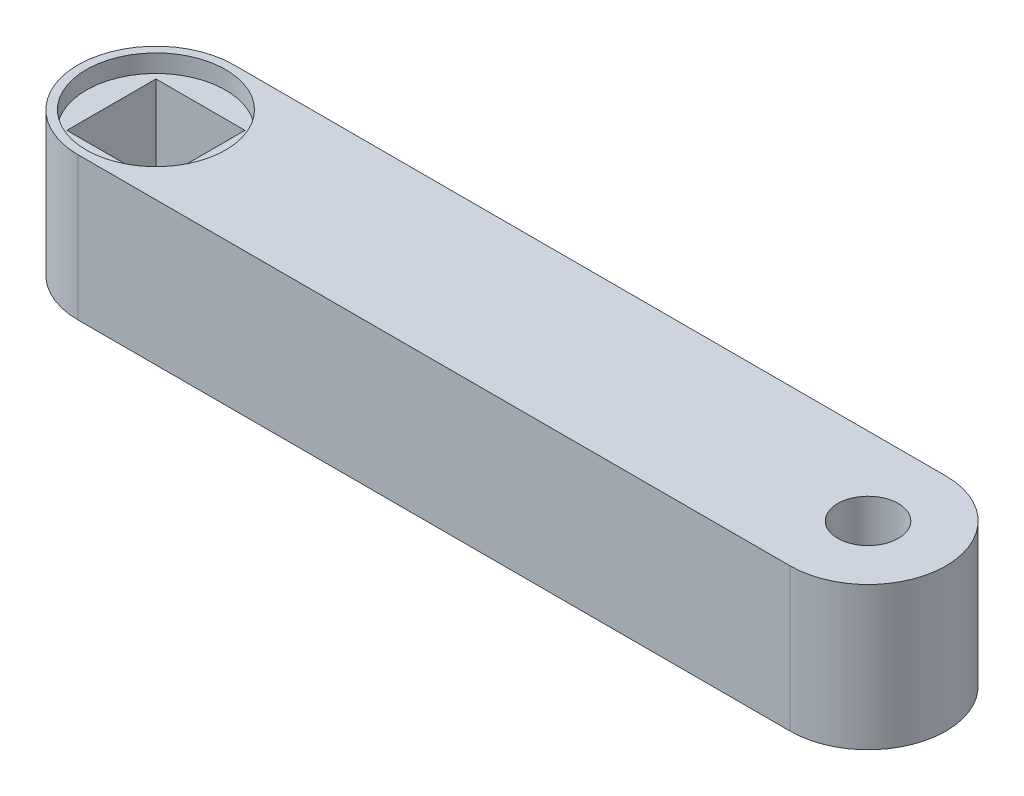
SolidWorks part; units mm, degrees
ref_plane "Front Plane" through (0, 0, 0) normal (0, 0, 1) x (1, 0, 0)
ref_plane "Top Plane" through (0, 0, 0) normal (0, 1, 0) x (1, 0, 0)
ref_plane "Right Plane" through (0, 0, 0) normal (1, 0, 0) x (0, 0, -1)
sketch "Sketch1" plane through (0, 0, 0) normal (0, 1, 0) x (1, 0, 0)
  line L0 (0, 0) -> (50.8, 0) construction
  line L1 (0, 5.5563) -> (50.8, 5.5563)
  line L2 (0, -5.5563) -> (50.8, -5.5563)
  arc A1 (0, 5.5563) -> (0, -5.5563) centre (0, 0) ccw
  arc A2 (50.8, -5.5563) -> (50.8, 5.5563) centre (50.8, 0) ccw
  point P3 (25.4, 0)
  dimension "D1" = 11.1125
  dimension "D2" = 50.8
extrude "Boss-Extrude1" add sketch "Sketch1" along normal blind 10.2108
sketch "Sketch2" plane through (0, 10.2108, 0) normal (0, 1, 0) x (1, 0, 0)
  line L1 (-3.175, 3.175) -> (3.175, 3.175)
  line L2 (-3.175, 3.175) -> (-3.175, -3.175)
  line L3 (-3.175, -3.175) -> (3.175, -3.175)
  line L4 (3.175, 3.175) -> (3.175, -3.175)
  line L5 (-3.175, 3.175) -> (3.175, -3.175) construction
  line L6 (-3.175, -3.175) -> (3.175, 3.175) construction
  circle A1 centre (50.8, 0) radius 2.159
  point P0 (0, 0)
  dimension "D2" = 6.35
  dimension "D3" = 4.318
  dimension "D1" = 6.35
  dimension "D4" = 50.8
extrude "Cut-Extrude1" cut sketch "Sketch2" against normal through all
sketch "Sketch3" plane through (0, 10.2108, 0) normal (0, 1, 0) x (1, 0, 0)
  circle A0 centre (0, 0) radius 4.9721
  dimension "D1" = 9.9441
extrude "Cut-Extrude2" cut sketch "Sketch3" against normal blind 1.27
ref_plane "Plane1" through (0, 5.1054, 0) normal (0, 1, 0) x (1, 0, 0)
mirror "Mirror1" about plane through (0, 5.1054, 0) normal (0, 1, 0) of "Cut-Extrude2"
